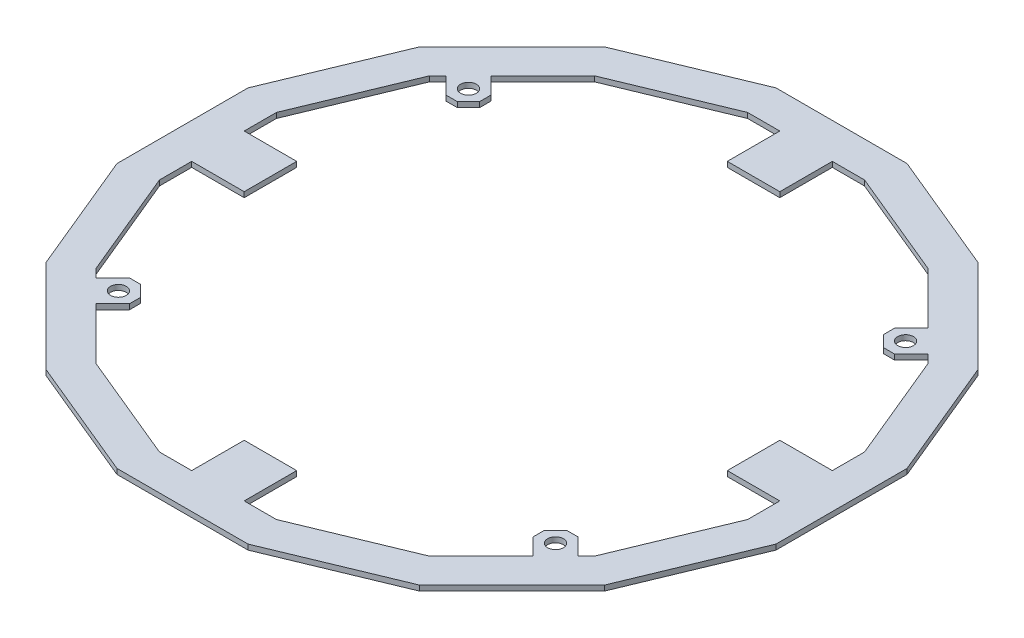
SolidWorks part; units mm, degrees
ref_plane "Front Plane" through (0, 0, 0) normal (0, 0, 1) x (1, 0, 0)
ref_plane "Top Plane" through (0, 0, 0) normal (0, 1, 0) x (1, 0, 0)
ref_plane "Right Plane" through (0, 0, 0) normal (1, 0, 0) x (0, 0, -1)
sketch "Sketch1" plane through (0, 0, 0) normal (0, 1, 0) x (1, 0, 0)
  line L1 (56, -11.1391) -> (56, 11.1391)
  line L2 (56, 11.1391) -> (47.4745, 31.7215)
  line L3 (47.4745, 31.7215) -> (31.7215, 47.4745)
  line L4 (31.7215, 47.4745) -> (11.1391, 56)
  line L5 (11.1391, 56) -> (-11.1391, 56)
  line L6 (-11.1391, 56) -> (-31.7215, 47.4745)
  line L7 (-31.7215, 47.4745) -> (-47.4745, 31.7215)
  line L8 (-47.4745, 31.7215) -> (-56, 11.1391)
  line L9 (-56, 11.1391) -> (-56, -11.1391)
  line L10 (-56, -11.1391) -> (-47.4745, -31.7215)
  line L11 (-47.4745, -31.7215) -> (-31.7215, -47.4745)
  line L12 (-31.7215, -47.4745) -> (-11.1391, -56)
  line L13 (-11.1391, -56) -> (11.1391, -56)
  line L14 (11.1391, -56) -> (31.7215, -47.4745)
  line L15 (31.7215, -47.4745) -> (47.4745, -31.7215)
  line L16 (47.4745, -31.7215) -> (56, -11.1391)
  line L17 (62.75, -12.4818) -> (62.75, 12.4818)
  line L18 (62.75, 12.4818) -> (53.1969, 35.545)
  line L19 (53.1969, 35.545) -> (35.545, 53.1969)
  line L20 (35.545, 53.1969) -> (12.4818, 62.75)
  line L21 (12.4818, 62.75) -> (-12.4818, 62.75)
  line L22 (-12.4818, 62.75) -> (-35.545, 53.1969)
  line L23 (-35.545, 53.1969) -> (-53.1969, 35.545)
  line L24 (-53.1969, 35.545) -> (-62.75, 12.4818)
  line L25 (-62.75, 12.4818) -> (-62.75, -12.4818)
  line L26 (-62.75, -12.4818) -> (-53.1969, -35.545)
  line L27 (-53.1969, -35.545) -> (-35.545, -53.1969)
  line L28 (-35.545, -53.1969) -> (-12.4818, -62.75)
  line L29 (-12.4818, -62.75) -> (12.4818, -62.75)
  line L30 (12.4818, -62.75) -> (35.545, -53.1969)
  line L31 (35.545, -53.1969) -> (53.1969, -35.545)
  line L32 (53.1969, -35.545) -> (62.75, -12.4818)
  circle A0 centre (0, 0) radius 56 construction
  circle A1 centre (0, 0) radius 62.75 construction
  dimension "D1" = 112
  dimension "D2" = 125.5
extrude "Boss-Extrude1" add sketch "Sketch1" along normal blind 1
sketch "Sketch2" plane through (0, 1, 0) normal (0, 1, 0) x (1, 0, 0)
  line L0 (11.1391, 56) -> (-11.1391, 56) construction
  line L1 (-5, 56) -> (5, 56)
  line L2 (-5, 56) -> (-5, 46)
  line L3 (-5, 46) -> (5, 46)
  line L4 (5, 56) -> (5, 46)
  line L5 (56, 5) -> (46, 5)
  line L6 (56, 5) -> (56, -5)
  line L7 (56, -5) -> (46, -5)
  line L8 (46, 5) -> (46, -5)
  line L9 (5, -56) -> (5, -46)
  line L10 (5, -56) -> (-5, -56)
  line L11 (-5, -56) -> (-5, -46)
  line L12 (5, -46) -> (-5, -46)
  line L13 (-56, -5) -> (-46, -5)
  line L14 (-56, -5) -> (-56, 5)
  line L15 (-56, 5) -> (-46, 5)
  line L16 (-46, -5) -> (-46, 5)
  point P6 (0, 56)
  point P22 (0, 0)
  dimension "D1" = 10
  dimension "D2" = 10
  dimension "D3" = 4
extrude "Boss-Extrude2" add sketch "Sketch2" against normal up to surface (1 mm away) up to face at (0, 0, 0)
sketch "Sketch3" plane through (0, 1, 0) normal (0, 1, 0) x (1, 0, 0)
  line L0 (-45.8636, 33.3324) -> (-41.6209, 37.575)
  line L1 (-31.7215, 47.4745) -> (-47.4745, 31.7215) construction
  line L2 (-41.6209, 37.575) -> (-37.3783, 33.3324)
  line L3 (-37.3783, 33.3324) -> (-41.6209, 29.0897)
  line L4 (-41.6209, 29.0897) -> (-45.8636, 33.3324)
  line L17 (0, 46) -> (0, -46) construction
  line L18 (-5, 46) -> (5, 46) construction
  line L19 (5, -46) -> (-5, -46) construction
  line L20 (-46, 0) -> (46, 0) construction
  line L21 (-46, -5) -> (-46, 5) construction
  line L22 (46, 5) -> (46, -5) construction
  line L23 (37.3783, 33.3324) -> (41.6209, 29.0897)
  line L24 (41.6209, 37.575) -> (37.3783, 33.3324)
  line L25 (45.8636, 33.3324) -> (41.6209, 37.575)
  line L26 (41.6209, 29.0897) -> (45.8636, 33.3324)
  line L27 (41.6209, -37.575) -> (37.3783, -33.3324)
  line L28 (45.8636, -33.3324) -> (41.6209, -37.575)
  line L29 (41.6209, -29.0897) -> (45.8636, -33.3324)
  line L30 (37.3783, -33.3324) -> (41.6209, -29.0897)
  line L31 (-37.3783, -33.3324) -> (-41.6209, -29.0897)
  line L32 (-41.6209, -37.575) -> (-37.3783, -33.3324)
  line L33 (-45.8636, -33.3324) -> (-41.6209, -37.575)
  line L34 (-41.6209, -29.0897) -> (-45.8636, -33.3324)
  circle A0 centre (-41.6209, 33.3324) radius 1.5
  circle A1 centre (41.6209, 33.3324) radius 1.5
  circle A2 centre (41.6209, -33.3324) radius 1.5
  circle A3 centre (-41.6209, -33.3324) radius 1.5
  point P23 (0, 0)
  dimension "D2" = 3
  dimension "D4" = 3
  dimension "D5" = 3
  dimension "D1" = 6
  dimension "D3" = 20
extrude "Boss-Extrude3" add sketch "Sketch3" against normal up to surface (1 mm away) up to face at (0, 0, 0)
chamfer "Chamfer1" distance 1.5 8 edges at (37.3783, 0.5, 33.3324) (41.6209, 0.5, 29.0897) (-41.6209, 0.5, 29.0897) (-37.3783, 0.5, 33.3324) (-37.3783, 0.5, -33.3324) (-41.6209, 0.5, -29.0897) (37.3783, 0.5, -33.3324) (41.6209, 0.5, -29.0897)
